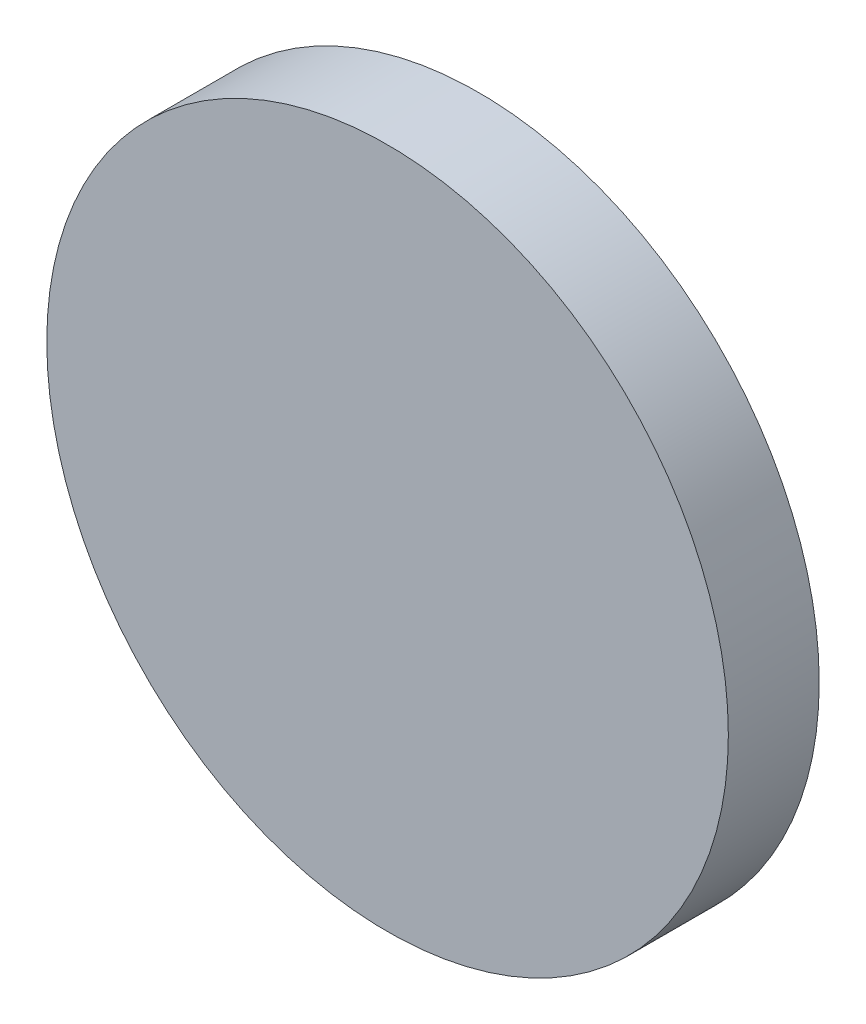
SolidWorks part; units mm, degrees
ref_plane "前视基准面" through (0, 0, 0) normal (0, 0, 1) x (1, 0, 0)
ref_plane "上视基准面" through (0, 0, 0) normal (0, 1, 0) x (1, 0, 0)
ref_plane "右视基准面" through (0, 0, 0) normal (1, 0, 0) x (0, 0, -1)
sketch "草图1" plane through (0, 0, 0) normal (0, 0, 1) x (1, 0, 0)
  circle A0 centre (0, 0) radius 3.75
  dimension "D1" = 7.5
extrude "凸台-拉伸1" add sketch "草图1" along normal blind 1
